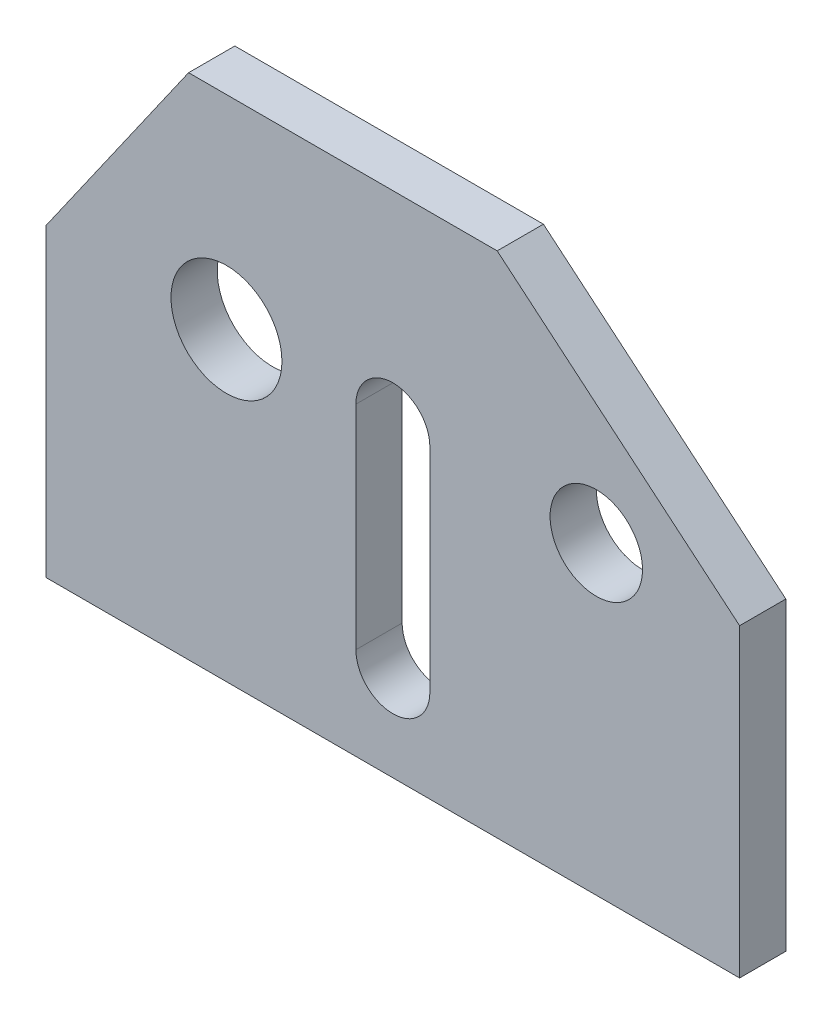
SolidWorks part; units mm, degrees
ref_plane "Płaszczyzna przednia" through (0, 0, 0) normal (0, 0, 1) x (1, 0, 0)
ref_plane "Płaszczyzna górna" through (0, 0, 0) normal (0, 1, 0) x (1, 0, 0)
ref_plane "Płaszczyzna prawa" through (0, 0, 0) normal (1, 0, 0) x (0, 0, -1)
sketch "Szkic1" plane through (0, 0, 0) normal (0, 0, 1) x (1, 0, 0)
  line L0 (0, 0) -> (75, 0)
  line L1 (75, 0) -> (75, 33)
  line L2 (75, 33) -> (48.7814, 55)
  line L3 (48.7814, 55) -> (15.4046, 55)
  line L4 (15.4046, 55) -> (0, 33)
  line L5 (0, 33) -> (0, 0)
  line L6 (33.5, 33) -> (33.5, 10)
  line L7 (41.5, 33) -> (41.5, 10)
  line L8 (37.5, 0) -> (37.5, 33) construction
  circle A0 centre (19.5, 33) radius 6
  circle A1 centre (59.5, 33) radius 5
  arc A2 (33.5, 10) -> (41.5, 10) centre (37.5, 10) ccw
  arc A3 (33.5, 33) -> (41.5, 33) centre (37.5, 33) cw
  point P17 (0, 0)
  point P18 (0, 0)
  point P21 (0, 0)
  dimension "D6" = 12
  dimension "D7" = 10
  dimension "D9" = 4
  dimension "D10" = 18
  dimension "D1" = 75
  dimension "D2" = 33
  dimension "D3" = 50
  dimension "D4" = 35
  dimension "D5" = 55
  dimension "D8" = 33
  dimension "D11" = 22
  dimension "D12" = 33
  dimension "D13" = 23
extrude "Dodanie-wyciągnięcie1" add sketch "Szkic1" along normal blind 5
